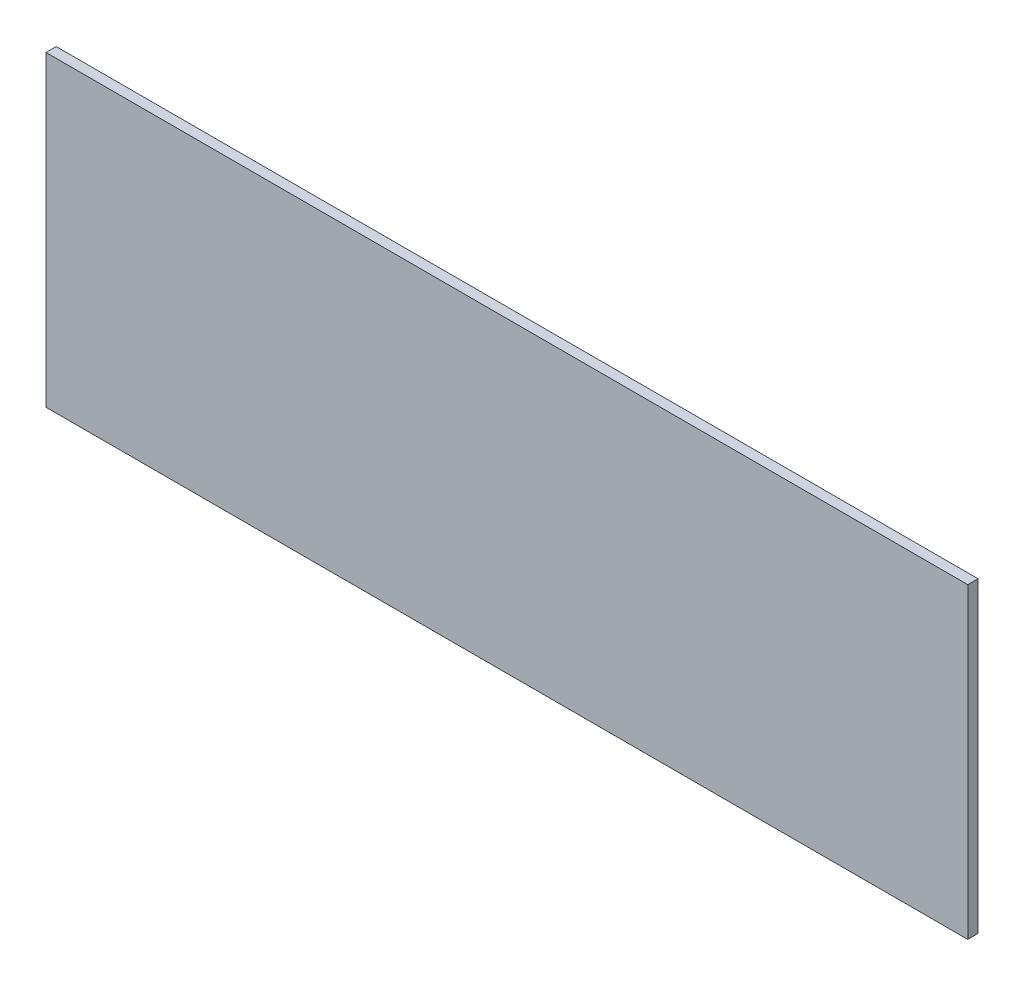
SolidWorks part; units mm, degrees
ref_plane "Front Plane" through (0, 0, 0) normal (0, 0, 1) x (1, 0, 0)
ref_plane "Top Plane" through (0, 0, 0) normal (0, 1, 0) x (1, 0, 0)
ref_plane "Right Plane" through (0, 0, 0) normal (1, 0, 0) x (0, 0, -1)
sketch "Sketch1" plane through (0, 0, 0) normal (0, 0, 1) x (1, 0, 0)
  line L2 (-60.2542, 46.9068) -> (29.7458, 46.9068)
  line L3 (-60.2542, 46.9068) -> (-60.2542, 16.9068)
  line L4 (-60.2542, 16.9068) -> (29.7458, 16.9068)
  line L5 (29.7458, 46.9068) -> (29.7458, 16.9068)
  dimension "D1" = 90
  dimension "D2" = 30
extrude "Boss-Extrude1" add sketch "Sketch1" along normal blind 1
